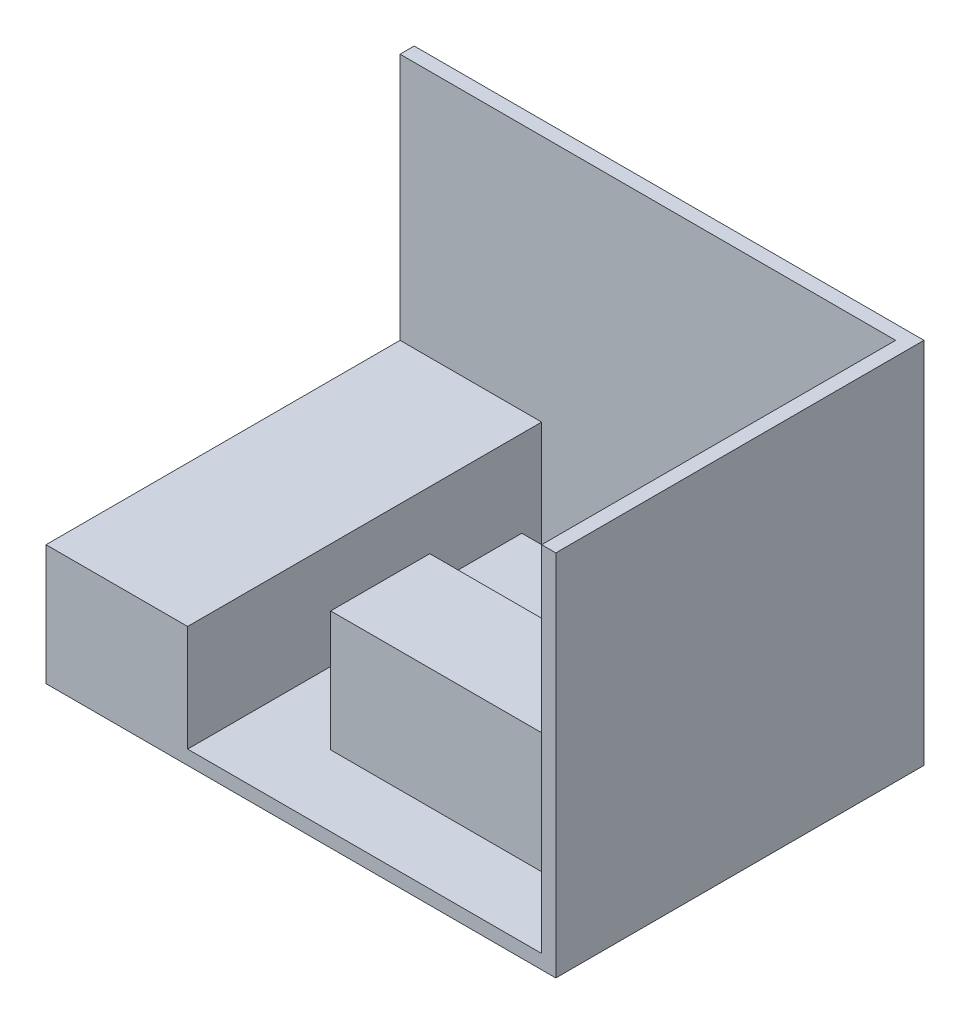
SolidWorks part; units mm, degrees
ref_plane "Front Plane" through (0, 0, 0) normal (0, 0, 1) x (1, 0, 0)
ref_plane "Top Plane" through (0, 0, 0) normal (0, 1, 0) x (1, 0, 0)
ref_plane "Right Plane" through (0, 0, 0) normal (1, 0, 0) x (0, 0, -1)
sketch "Sketch1" plane through (0, 0, 0) normal (0, 1, 0) x (1, 0, 0)
  line L1 (0, 2600) -> (3600, 2600)
  line L2 (0, 2600) -> (0, 0)
  line L3 (0, 0) -> (3600, 0)
  line L4 (3600, 2600) -> (3600, 0)
  point P4 (0, 0)
  dimension "D1" = 3600
  dimension "D2" = 2600
extrude "Boss-Extrude1" add sketch "Sketch1" along normal blind 100
sketch "Sketch2" plane through (0, 100, 0) normal (0, 1, 0) x (1, 0, 0)
  line L0 (3600, 0) -> (3500, 0)
  line L1 (0, 0) -> (3600, 0) construction
  line L2 (3500, 0) -> (3500, 2500)
  line L3 (3500, 2500) -> (0, 2500)
  line L4 (0, 2600) -> (0, 0) construction
  line L5 (0, 2500) -> (0, 2600)
  line L6 (0, 2600) -> (3600, 2600)
  line L7 (3600, 2600) -> (3600, 0)
  dimension "D1" = 100
  dimension "D2" = 100
extrude "Boss-Extrude2" add sketch "Sketch2" along normal blind 2500
sketch "Sketch4" plane through (0, 100, 0) normal (0, 1, 0) x (1, 0, 0)
  line L0 (0, 0) -> (3500, 0) construction
  line L1 (3510, 500) -> (1510, 500)
  line L2 (3510, 500) -> (3510, 1200)
  line L3 (3510, 1200) -> (1510, 1200)
  line L4 (1510, 500) -> (1510, 1200)
  line L6 (3500, 2500) -> (3500, 0) construction
  dimension "D1" = 2000
  dimension "D2" = 700
  dimension "D3" = 500
  dimension "D4" = 10
extrude "Boss-Extrude3" add sketch "Sketch4" along normal blind 850
sketch "Sketch5" plane through (0, 100, 0) normal (0, 1, 0) x (1, 0, 0)
  line L0 (0, 2500) -> (3500, 2500) construction
  line L1 (0, 0) -> (1000, 0)
  line L2 (0, 0) -> (0, 2500)
  line L3 (0, 2500) -> (1000, 2500)
  line L4 (1000, 0) -> (1000, 2500)
  dimension "D1" = 1000
extrude "Boss-Extrude4" add sketch "Sketch5" along normal blind 750
sketch "Sketch6" plane through (0, 100, 0) normal (0, 1, 0) x (1, 0, 0)
  line L0 (3500, 1200) -> (1510, 1200) construction
  line L1 (1610, 1250) -> (2310, 1250)
  line L2 (1610, 1250) -> (1610, 1750)
  line L3 (1610, 1750) -> (2310, 1750)
  line L4 (2310, 1250) -> (2310, 1750)
  line L6 (1510, 1200) -> (1510, 500) construction
  dimension "D1" = 500
  dimension "D2" = 700
  dimension "D3" = 50
  dimension "D4" = 100
extrude "Boss-Extrude5" add sketch "Sketch6" along normal blind 750
